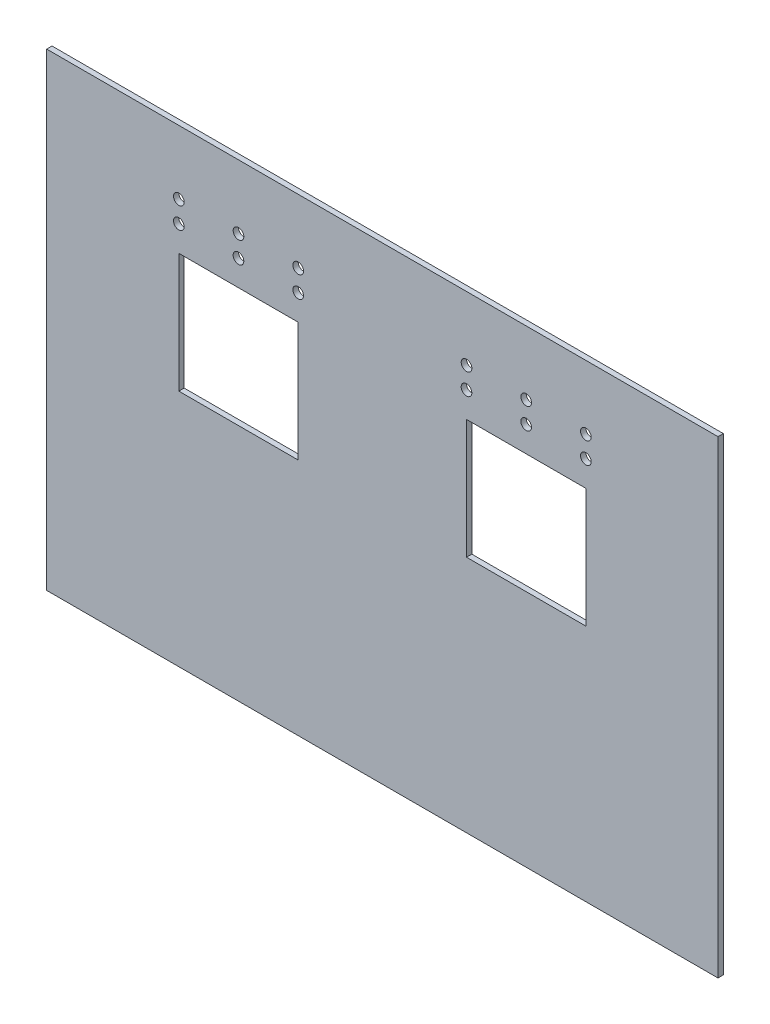
SolidWorks part; units mm, degrees
material "Pine"
ref_plane "Front Plane" through (0, 0, 0) normal (0, 0, 1) x (1, 0, 0)
ref_plane "Top Plane" through (0, 0, 0) normal (0, 1, 0) x (1, 0, 0)
ref_plane "Right Plane" through (0, 0, 0) normal (1, 0, 0) x (0, 0, -1)
sketch "Sketch1" plane through (0, 0, 0) normal (0, 0, 1) x (1, 0, 0)
  line L0 (0, 139.7) -> (0, -144.7888) construction
  line L1 (-200.025, 139.7) -> (200.025, 139.7)
  line L2 (-200.025, 139.7) -> (-200.025, -139.7)
  line L3 (-200.025, -139.7) -> (200.025, -139.7)
  line L4 (200.025, 139.7) -> (200.025, -139.7)
  line L5 (-200.025, 139.7) -> (200.025, -139.7) construction
  line L6 (-200.025, -139.7) -> (200.025, 139.7) construction
  line L7 (-121.285, 73.66) -> (-50.165, 73.66)
  line L8 (-121.285, 73.66) -> (-121.285, 2.54)
  line L9 (-121.285, 2.54) -> (-50.165, 2.54)
  line L10 (-50.165, 73.66) -> (-50.165, 2.54)
  line L11 (-121.285, 73.66) -> (-50.165, 2.54) construction
  line L12 (-121.285, 2.54) -> (-50.165, 73.66) construction
  line L13 (121.285, 2.54) -> (50.165, 2.54)
  line L14 (50.165, 73.66) -> (50.165, 2.54)
  line L15 (121.285, 73.66) -> (50.165, 73.66)
  line L16 (121.285, 73.66) -> (121.285, 2.54)
  circle A0 centre (-85.725, 88.9) radius 3.175
  circle A1 centre (-121.285, 88.9) radius 3.175
  circle A2 centre (-50.165, 88.9) radius 3.175
  circle A3 centre (-50.165, 101.6) radius 3.175
  circle A4 centre (-85.725, 101.6) radius 3.175
  circle A5 centre (-121.285, 101.6) radius 3.175
  circle A6 centre (121.285, 88.9) radius 3.175
  circle A7 centre (85.725, 88.9) radius 3.175
  circle A8 centre (50.165, 88.9) radius 3.175
  circle A9 centre (50.165, 101.6) radius 3.175
  circle A10 centre (85.725, 101.6) radius 3.175
  circle A11 centre (121.285, 101.6) radius 3.175
  point P0 (0, 0)
  point P6 (-85.725, 38.1)
  point P21 (-108.199, 113.4458)
  point P24 (-59.2483, 113.4458)
  point P27 (-59.2483, 125.0059)
  point P30 (-82.9082, 125.0059)
  point P33 (-108.199, 125.0059)
  point P34 (-121.285, 113.4458)
  point P35 (-121.285, 107.3754)
  point P36 (-121.285, 125.0059)
  point P37 (-85.725, 107.95)
  point P38 (-50.165, 107.95)
  point P39 (-85.725, 125.0059)
  point P40 (-50.165, 125.0059)
  point P41 (-85.725, 125.0059)
  point P42 (-50.165, 125.73)
  point P43 (-85.725, 118.11)
  point P44 (-50.165, 118.11)
  point P45 (-85.725, 120.65)
  point P46 (-50.165, 120.65)
  point P59 (-85.725, 88.9)
  point P60 (-85.725, 101.6)
  point P61 (-50.165, 88.9)
  point P62 (-50.165, 101.6)
  dimension "D7" = 6.35
  dimension "D1" = 400.05
  dimension "D2" = 279.4
  dimension "D3" = 71.12
  dimension "D4" = 71.12
  dimension "D5" = 101.6
  dimension "D6" = 114.3
  dimension "D8" = 50.8
  dimension "D9" = 12.7
extrude "Boss-Extrude1" add sketch "Sketch1" along normal blind 3.175
